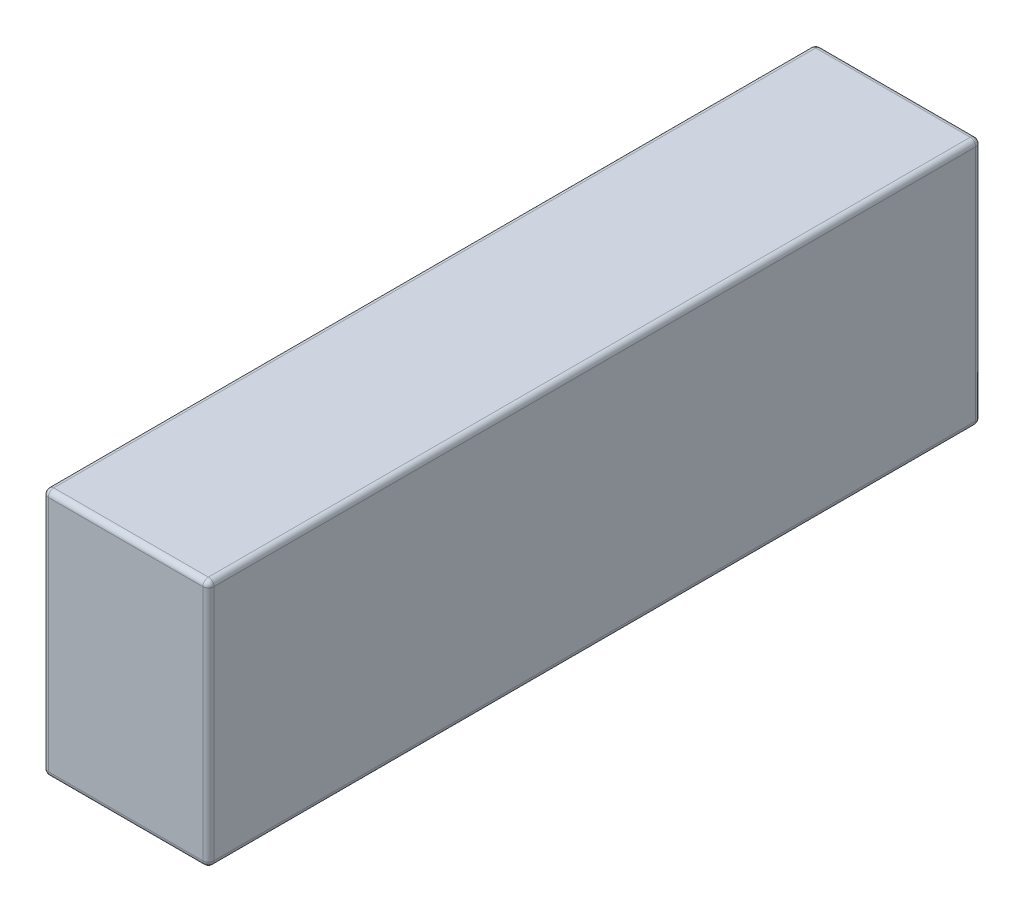
SolidWorks part; units mm, degrees
ref_plane "Front Plane" through (0, 0, 0) normal (0, 0, 1) x (1, 0, 0)
ref_plane "Top Plane" through (0, 0, 0) normal (0, 1, 0) x (1, 0, 0)
ref_plane "Right Plane" through (0, 0, 0) normal (1, 0, 0) x (0, 0, -1)
sketch "Sketch1" plane through (0, 0, 0) normal (0, 1, 0) x (1, 0, 0)
  line L1 (15, -70) -> (-15, -70)
  line L2 (15, -70) -> (15, 70)
  line L3 (15, 70) -> (-15, 70)
  line L4 (-15, -70) -> (-15, 70)
  line L5 (15, -70) -> (-15, 70) construction
  line L6 (15, 70) -> (-15, -70) construction
  point P0 (0, 0)
  dimension "D1" = 30
  dimension "D2" = 140
extrude "Boss-Extrude1" add sketch "Sketch1" along normal blind 45
fillet "Fillet1" radius 1 12 edges at (0, 0, -70) (-15, 22.5, -70) (-15, 0, 0) (-15, 22.5, 70) (0, 0, 70) (0, 45, -70) (0, 45, 70) (-15, 45, 0) (15, 22.5, 70) (15, 45, 0) (15, 22.5, -70) (15, 0, 0)
